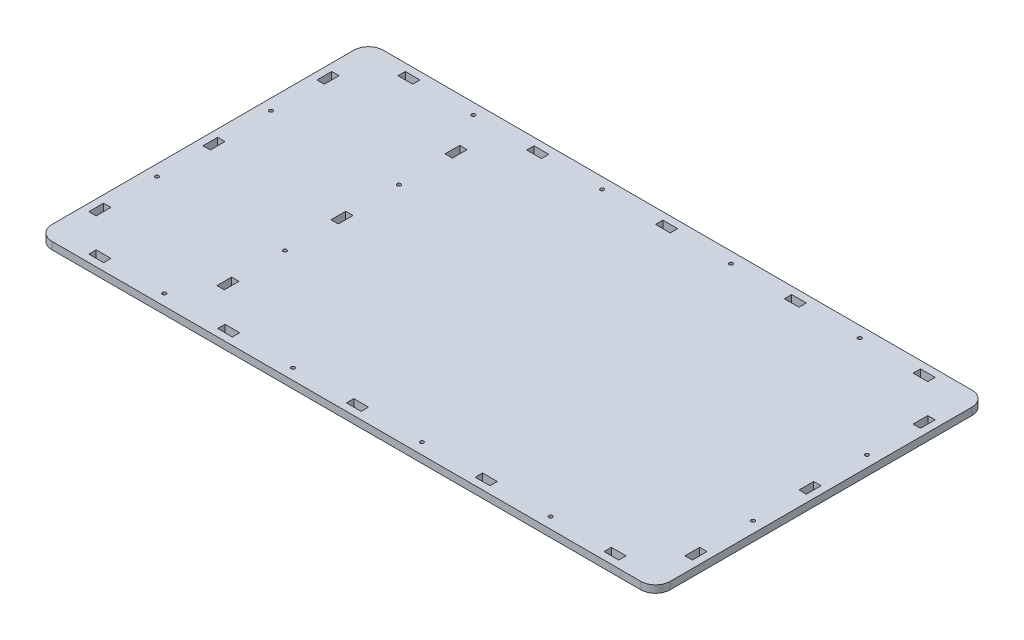
SolidWorks part; units mm, degrees
ref_plane "Front Plane" through (0, 0, 0) normal (0, 0, 1) x (1, 0, 0)
ref_plane "Top Plane" through (0, 0, 0) normal (0, 1, 0) x (1, 0, 0)
ref_plane "Right Plane" through (0, 0, 0) normal (1, 0, 0) x (0, 0, -1)
sketch "Sketch1" plane through (0, 0, 0) normal (0, 1, 0) x (1, 0, 0)
  line L1 (-210, 112.5) -> (210, 112.5)
  line L2 (-210, 112.5) -> (-210, -112.5)
  line L3 (-210, -112.5) -> (210, -112.5)
  line L4 (210, 112.5) -> (210, -112.5)
  line L5 (-210, 112.5) -> (210, -112.5) construction
  line L6 (-210, -112.5) -> (210, 112.5) construction
  point P0 (0, 0)
  dimension "D1" = 420
  dimension "D2" = 225
extrude "Boss-Extrude1" add sketch "Sketch1" along normal blind 5
sketch "Sketch2" plane through (0, 5, 0) normal (0, 1, 0) x (1, 0, 0)
  line L0 (0, 0) -> (0, -50000) construction
  line L1 (0, 0) -> (50000, 0) construction
  line L2 (-185.1212, 107.5) -> (49814.8788, 107.5) construction
  line L3 (205, -72.5) -> (205, -82.5)
  line L4 (-205, 90.9978) -> (-205, -49909.0022) construction
  line L5 (-92.5, 107.5) -> (-92.5, 102.5)
  line L6 (-180, 107.5) -> (-170, 107.5)
  line L7 (-180, 107.5) -> (-180, 102.5)
  line L8 (-180, 102.5) -> (-170, 102.5)
  line L9 (-170, 107.5) -> (-170, 102.5)
  line L10 (-205, 82.5) -> (-200, 82.5)
  line L11 (-205, 82.5) -> (-205, 72.5)
  line L12 (-205, 72.5) -> (-200, 72.5)
  line L13 (-200, 82.5) -> (-200, 72.5)
  line L14 (-92.5, 102.5) -> (-82.5, 102.5)
  line L15 (-82.5, 107.5) -> (-82.5, 102.5)
  line L16 (-92.5, 107.5) -> (-82.5, 107.5)
  line L17 (-5, 107.5) -> (-5, 102.5)
  line L18 (-5, 102.5) -> (5, 102.5)
  line L19 (5, 107.5) -> (5, 102.5)
  line L20 (-5, 107.5) -> (5, 107.5)
  line L21 (82.5, 107.5) -> (82.5, 102.5)
  line L22 (82.5, 102.5) -> (92.5, 102.5)
  line L23 (92.5, 107.5) -> (92.5, 102.5)
  line L24 (82.5, 107.5) -> (92.5, 107.5)
  line L25 (170, 107.5) -> (170, 102.5)
  line L26 (170, 102.5) -> (180, 102.5)
  line L27 (180, 107.5) -> (180, 102.5)
  line L28 (170, 107.5) -> (180, 107.5)
  line L29 (210, 112.5) -> (-210, 112.5) construction
  line L30 (-210, 112.5) -> (-210, -112.5) construction
  line L31 (-205, 5) -> (-200, 5)
  line L32 (-200, 5) -> (-200, -5)
  line L33 (-205, -5) -> (-200, -5)
  line L34 (-205, 5) -> (-205, -5)
  line L35 (-205, -72.5) -> (-200, -72.5)
  line L36 (-200, -72.5) -> (-200, -82.5)
  line L37 (-205, -82.5) -> (-200, -82.5)
  line L38 (-205, -72.5) -> (-205, -82.5)
  line L39 (205, -82.5) -> (200, -82.5)
  line L40 (200, -72.5) -> (200, -82.5)
  line L41 (205, -72.5) -> (200, -72.5)
  line L42 (205, 5) -> (205, -5)
  line L43 (205, -5) -> (200, -5)
  line L44 (200, 5) -> (200, -5)
  line L45 (205, 5) -> (200, 5)
  line L46 (200, 82.5) -> (200, 72.5)
  line L47 (205, 72.5) -> (200, 72.5)
  line L48 (205, 82.5) -> (205, 72.5)
  line L49 (205, 82.5) -> (200, 82.5)
  line L50 (170, -107.5) -> (180, -107.5)
  line L51 (180, -107.5) -> (180, -102.5)
  line L52 (170, -102.5) -> (180, -102.5)
  line L53 (170, -107.5) -> (170, -102.5)
  line L54 (82.5, -107.5) -> (92.5, -107.5)
  line L55 (92.5, -107.5) -> (92.5, -102.5)
  line L56 (82.5, -102.5) -> (92.5, -102.5)
  line L57 (82.5, -107.5) -> (82.5, -102.5)
  line L58 (-5, -107.5) -> (5, -107.5)
  line L59 (5, -107.5) -> (5, -102.5)
  line L60 (-5, -102.5) -> (5, -102.5)
  line L61 (-5, -107.5) -> (-5, -102.5)
  line L62 (-92.5, -107.5) -> (-82.5, -107.5)
  line L63 (-82.5, -107.5) -> (-82.5, -102.5)
  line L64 (-92.5, -102.5) -> (-82.5, -102.5)
  line L65 (-170, -107.5) -> (-170, -102.5)
  line L66 (-180, -102.5) -> (-170, -102.5)
  line L67 (-180, -107.5) -> (-180, -102.5)
  line L68 (-180, -107.5) -> (-170, -107.5)
  line L69 (-92.5, -107.5) -> (-92.5, -102.5)
  line L70 (-159, 27.2028) -> (-159, -49972.7972) construction
  line L71 (-113, 82.5) -> (-113, 72.5)
  line L72 (-118, 82.5) -> (-118, 72.5)
  line L73 (-113, 82.5) -> (-118, 82.5)
  line L74 (-113, -72.5) -> (-113, -82.5)
  line L75 (-113, -82.5) -> (-118, -82.5)
  line L76 (-118, -72.5) -> (-118, -82.5)
  line L77 (-113, -72.5) -> (-118, -72.5)
  line L78 (-113, 5) -> (-113, -5)
  line L79 (-113, -5) -> (-118, -5)
  line L80 (-118, 5) -> (-118, -5)
  line L81 (-113, 5) -> (-118, 5)
  line L82 (-113, 72.5) -> (-118, 72.5)
  dimension "D2" = 5
  dimension "D3" = 5
  dimension "D4" = 10
  dimension "D5" = 5
  dimension "D6" = 25
  dimension "D8" = 25
  dimension "D9" = 87
  dimension "D1" = 5
  dimension "D7" = 3
extrude "Cut-Extrude1" cut sketch "Sketch2" against normal through all
fillet "Fillet1" radius 10 4 edges at (-210, 2.5, 112.5) (210, 2.5, 112.5) (210, 2.5, -112.5) (-210, 2.5, -112.5)
sketch "Sketch3" plane through (0, 5, 0) normal (0, 1, 0) x (1, 0, 0)
  line L0 (-170, 105) -> (-92.5, 105) construction
  line L1 (-170, 102.5) -> (-170, 107.5) construction
  line L2 (-92.5, 107.5) -> (-92.5, 102.5) construction
  line L3 (-82.5, 105) -> (-5, 105) construction
  line L4 (-82.5, 102.5) -> (-82.5, 107.5) construction
  line L5 (-5, 107.5) -> (-5, 102.5) construction
  line L6 (-202.5, 72.5) -> (-202.5, 5) construction
  line L7 (-205, 72.5) -> (-200, 72.5) construction
  line L8 (-200, 5) -> (-205, 5) construction
  line L9 (-202.5, 5) -> (-202.5, -5) construction
  line L10 (-205, -5) -> (-200, -5) construction
  line L11 (-202.5, -5) -> (-202.5, -72.5) construction
  line L12 (-200, -72.5) -> (-205, -72.5) construction
  line L13 (-202.5, -72.5) -> (-115.5, -72.5) construction
  line L14 (-113, -72.5) -> (-118, -72.5) construction
  line L15 (-159, -72.5) -> (-159, -50072.5) construction
  line L16 (0, 0) -> (-50000, 0) construction
  line L17 (0, 0) -> (0, -50000) construction
  circle A0 centre (-131.25, 105) radius 1.25
  circle A1 centre (-202.5, 38.75) radius 1.25
  circle A2 centre (-202.5, -38.75) radius 1.25
  circle A3 centre (-43.75, 105) radius 1.25
  circle A4 centre (43.75, 105) radius 1.25
  circle A5 centre (131.25, 105) radius 1.25
  circle A6 centre (-115.5, -38.75) radius 1.25
  circle A7 centre (-115.5, 38.75) radius 1.25
  circle A8 centre (202.5, -38.75) radius 1.25
  circle A9 centre (202.5, 38.75) radius 1.25
  circle A10 centre (131.25, -105) radius 1.25
  circle A11 centre (43.75, -105) radius 1.25
  circle A12 centre (-43.75, -105) radius 1.25
  circle A13 centre (-131.25, -105) radius 1.25
  point P35 (-159, -72.5)
  dimension "D1" = 2.5
  dimension "D2" = 4
extrude "Cut-Extrude2" cut sketch "Sketch3" against normal through all
